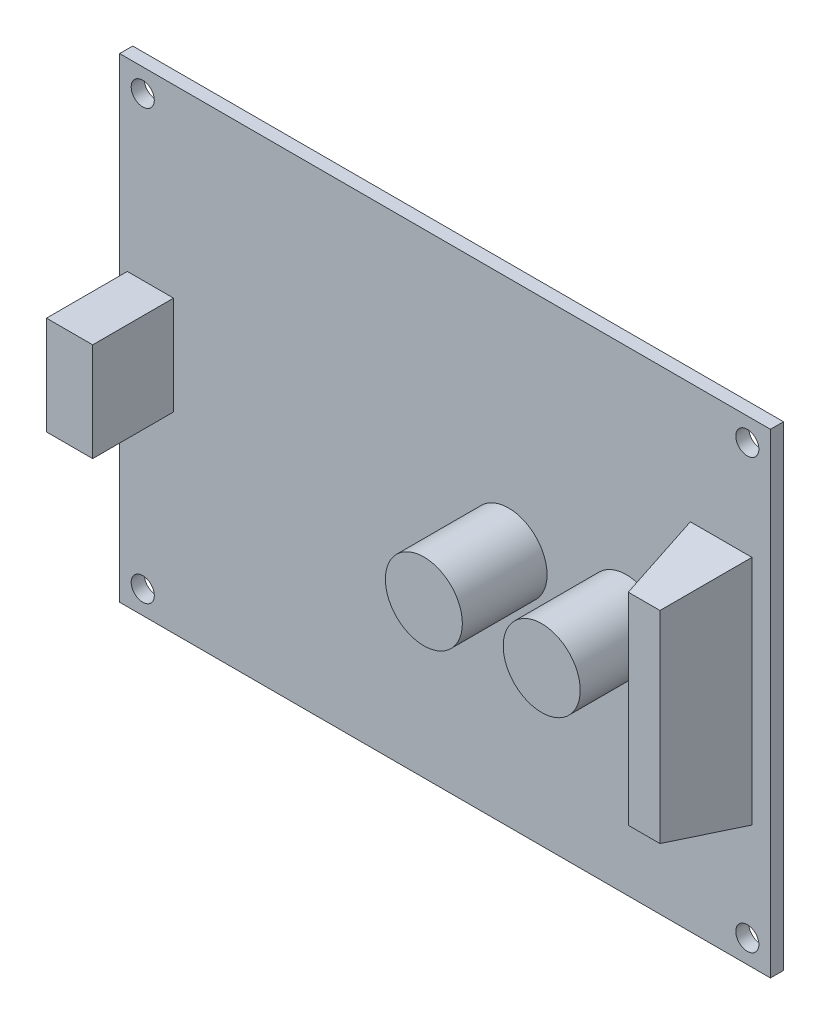
SolidWorks part; units mm, degrees
ref_plane "Front Plane" through (0, 0, 0) normal (0, 0, 1) x (1, 0, 0)
ref_plane "Top Plane" through (0, 0, 0) normal (0, 1, 0) x (1, 0, 0)
ref_plane "Right Plane" through (0, 0, 0) normal (1, 0, 0) x (0, 0, -1)
sketch "Sketch1" plane through (0, 0, 0) normal (0, 0, 1) x (1, 0, 0)
  line L1 (-31.097, 42.74) -> (53.403, 42.74)
  line L2 (-31.097, 42.74) -> (-31.097, -18.96)
  line L3 (-31.097, -18.96) -> (53.403, -18.96)
  line L4 (53.403, 42.74) -> (53.403, -18.96)
  dimension "D1" = 84.5
  dimension "D2" = 61.7
extrude "Boss-Extrude1" add sketch "Sketch1" along normal blind 1.7
sketch "Sketch2" plane through (0, 0, 1.7) normal (0, 0, 1) x (1, 0, 0)
  line L0 (53.403, -18.96) -> (53.403, 42.74) construction
  line L1 (43.003, 27.14) -> (51.003, 27.14)
  line L2 (43.003, 27.14) -> (43.003, -2.96)
  line L3 (43.003, -2.96) -> (51.003, -2.96)
  line L4 (51.003, 27.14) -> (51.003, -2.96)
  line L5 (53.403, 42.74) -> (-31.097, 42.74) construction
  point P4 (47.003, 27.14)
  dimension "D1" = 30.1
  dimension "D2" = 8
  dimension "D3" = 2.4
  dimension "D4" = 15.6
extrude "Boss-Extrude2" add sketch "Sketch2" along normal blind 10 draft 11
sketch "Sketch3" plane through (0, 0, 1.7) normal (0, 0, 1) x (1, 0, 0)
  line L0 (53.403, 42.74) -> (-31.097, 42.74) construction
  line L3 (53.403, -18.96) -> (53.403, 42.74) construction
  circle A0 centre (19.403, 11.89) radius 5
  dimension "D1" = 10
  dimension "D2" = 30.85
  dimension "D3" = 34
extrude "Boss-Extrude3" add sketch "Sketch3" along normal blind 11
sketch "Sketch4" plane through (0, 0, 1.7) normal (0, 0, 1) x (1, 0, 0)
  line L0 (53.403, -18.96) -> (53.403, 42.74) construction
  line L1 (-31.097, -18.96) -> (53.403, -18.96) construction
  circle A0 centre (34.703, 12.04) radius 5
  dimension "D1" = 10
  dimension "D2" = 18.7
  dimension "D3" = 31
extrude "Boss-Extrude4" add sketch "Sketch4" along normal blind 11
sketch "Sketch5" plane through (0, 0, 1.7) normal (0, 0, 1) x (1, 0, 0)
  line L0 (-31.097, 42.74) -> (-31.097, -18.96) construction
  line L1 (-30.097, 18.74) -> (-24.097, 18.74)
  line L2 (-30.097, 18.74) -> (-30.097, 5.94)
  line L3 (-30.097, 5.94) -> (-24.097, 5.94)
  line L4 (-24.097, 18.74) -> (-24.097, 5.94)
  line L5 (53.403, 42.74) -> (-31.097, 42.74) construction
  point P8 (-27.097, 18.74)
  dimension "D1" = 1
  dimension "D2" = 24
  dimension "D3" = 6
  dimension "D4" = 12.8
extrude "Boss-Extrude5" add sketch "Sketch5" along normal blind 10.5
sketch "Sketch6" plane through (0, 0, 1.7) normal (0, 0, 1) x (1, 0, 0)
  line L0 (-31.097, 42.74) -> (-31.097, -18.96) construction
  line L1 (-31.097, -18.96) -> (53.403, -18.96) construction
  circle A0 centre (-28.097, -15.96) radius 1.5
  dimension "D1" = 3
  dimension "D2" = 3
  dimension "D3" = 3
extrude "Cut-Extrude1" cut sketch "Sketch6" against normal blind 10
sketch "Sketch7" plane through (0, 0, 1.7) normal (0, 0, 1) x (1, 0, 0)
  line L0 (53.403, 42.74) -> (-31.097, 42.74) construction
  line L1 (-31.097, 42.74) -> (-31.097, -18.96) construction
  circle A0 centre (-28.097, 39.74) radius 1.5
  dimension "D1" = 3
  dimension "D2" = 3
  dimension "D3" = 3
extrude "Cut-Extrude2" cut sketch "Sketch7" against normal blind 10
sketch "Sketch8" plane through (0, 0, 1.7) normal (0, 0, 1) x (1, 0, 0)
  line L0 (53.403, -18.96) -> (53.403, 42.74) construction
  line L1 (-31.097, -18.96) -> (53.403, -18.96) construction
  circle A0 centre (50.403, -15.96) radius 1.5
  dimension "D3" = 3
  dimension "D1" = 3
  dimension "D2" = 3
extrude "Cut-Extrude3" cut sketch "Sketch8" against normal blind 10
sketch "Sketch9" plane through (0, 0, 1.7) normal (0, 0, 1) x (1, 0, 0)
  line L0 (53.403, -18.96) -> (53.403, 42.74) construction
  line L1 (53.403, 42.74) -> (-31.097, 42.74) construction
  circle A0 centre (50.403, 39.74) radius 1.5
  point P6 (-96.8181, -70.4152)
  point P7 (-89.595, -77.1621)
  dimension "D3" = 3
  dimension "D1" = 3
  dimension "D2" = 3
extrude "Cut-Extrude4" cut sketch "Sketch9" against normal blind 10
